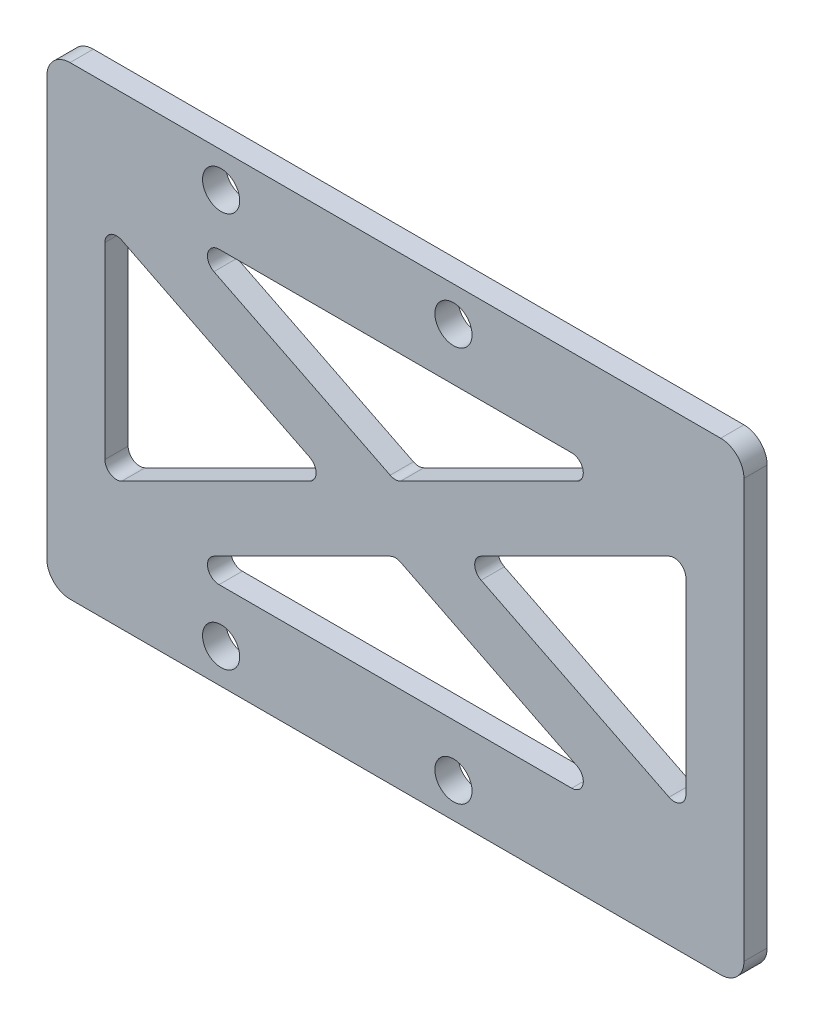
SolidWorks part; units mm, degrees
ref_plane "前视基准面" through (0, 0, 0) normal (0, 0, 1) x (1, 0, 0)
ref_plane "上视基准面" through (0, 0, 0) normal (0, 1, 0) x (1, 0, 0)
ref_plane "右视基准面" through (0, 0, 0) normal (1, 0, 0) x (0, 0, -1)
other "Configuration Table"
sketch "草图1" plane through (0, 0, 0) normal (0, 0, 1) x (1, 0, 0)
  line L1 (-30, 20) -> (30, 20)
  line L2 (-30, 20) -> (-30, -20)
  line L3 (-30, -20) -> (30, -20)
  line L4 (30, 20) -> (30, -20)
  line L5 (-30, 20) -> (30, -20) construction
  line L6 (-30, -20) -> (30, 20) construction
  point P0 (0, 0)
  dimension "D1" = 60
  dimension "D2" = 40
extrude "凸台-拉伸1" add sketch "草图1" along normal blind 2
fillet "圆角1" radius 2 4 edges at (-30, 20, 1) (-30, -20, 1) (30, -20, 1) (30, 20, 1)
sketch "草图2" plane through (0, 0, 2) normal (0, 0, 1) x (1, 0, 0)
  circle A0 centre (-15, 17) radius 1.6
  circle A1 centre (5, 17) radius 1.6
  circle A2 centre (5, -17) radius 1.6
  circle A3 centre (-15, -17) radius 1.6
extrude "切除-拉伸1" cut sketch "草图2" against normal through all
sketch "草图3" plane through (0, 0, 2) normal (0, 0, 1) x (1, 0, 0)
  line L0 (28, 20) -> (-28, 20) construction
  line L1 (-25, 12.5) -> (25, 12.5)
  line L2 (-25, 12.5) -> (-25, -12.5)
  line L3 (-25, -12.5) -> (25, -12.5)
  line L4 (25, 12.5) -> (25, -12.5)
  line L5 (-28, -20) -> (28, -20) construction
  line L6 (30, -18) -> (30, 18) construction
  line L7 (-30, 18) -> (-30, -18) construction
  line L8 (-25, 12.5) -> (25, -12.5) construction
  line L9 (-25, -12.5) -> (25, 12.5) construction
  line L10 (-26.118, 10.2639) -> (23.882, -14.7361)
  line L11 (-23.882, -14.7361) -> (26.118, 10.2639)
  line L12 (-23.882, 14.7361) -> (26.118, -10.2639)
  line L13 (-26.118, -10.2639) -> (23.882, 14.7361)
  dimension "D1" = 7.5
  dimension "D2" = 7.5
  dimension "D3" = 5
  dimension "D4" = 5
  dimension "D5" = 2.5
  dimension "D6" = 2.5
extrude "切除-拉伸2" cut sketch "草图3" against normal through all contours L2 L13 L10 | L12 L13 L1 | L11 L3 L10 | L11 L12 L4
fillet "圆角2" radius 1 12 edges at (-25, 9.7049, 1) (-5.5902, 0, 1) (-25, -9.7049, 1) (-19.4098, -12.5, 1) (0, -2.7951, 1) (19.4098, -12.5, 1) (5.5902, 0, 1) (25, -9.7049, 1) (25, 9.7049, 1) (19.4098, 12.5, 1) (-19.4098, 12.5, 1) (0, 2.7951, 1)
